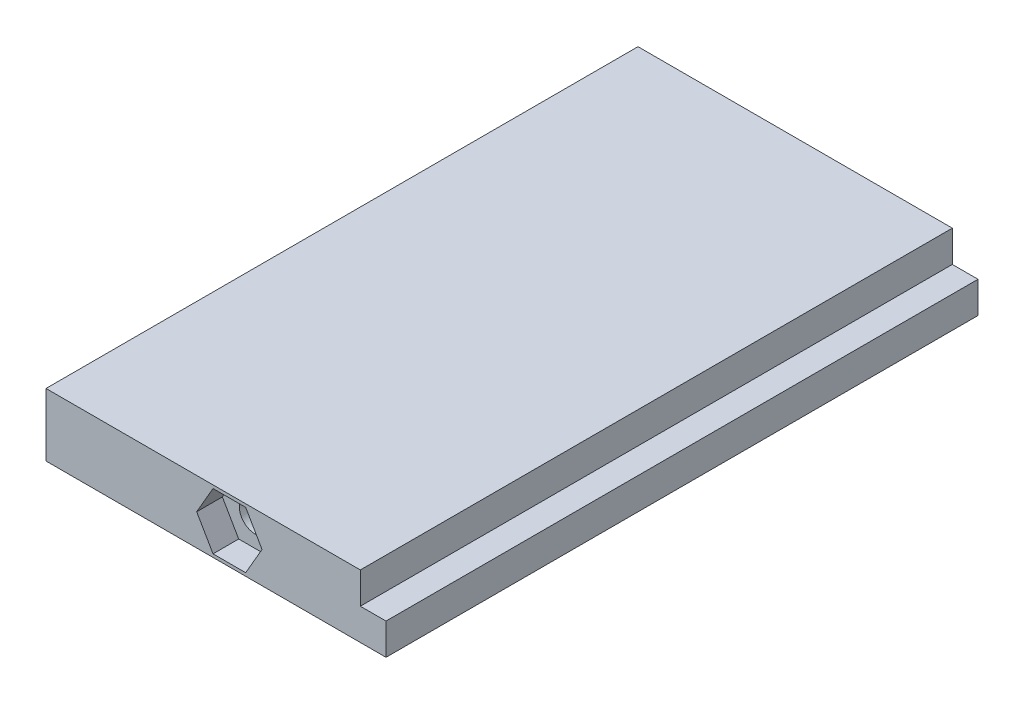
SolidWorks part; units mm, degrees
ref_plane "Front Plane" through (0, 0, 0) normal (0, 0, 1) x (1, 0, 0)
ref_plane "Top Plane" through (0, 0, 0) normal (0, 1, 0) x (1, 0, 0)
ref_plane "Right Plane" through (0, 0, 0) normal (1, 0, 0) x (0, 0, -1)
sketch "Sketch1" plane through (0, 0, 0) normal (0, 1, 0) x (1, 0, 0)
  line L1 (-15, 28.25) -> (15, 28.25)
  line L2 (-15, 28.25) -> (-15, -28.25)
  line L3 (-15, -28.25) -> (15, -28.25)
  line L4 (15, 28.25) -> (15, -28.25)
  line L5 (-15, 28.25) -> (15, -28.25) construction
  line L6 (-15, -28.25) -> (15, 28.25) construction
  point P4 (0, 0)
  point P5 (0, 0)
  point P6 (36.1808, 26.0547)
  point P7 (0, 0)
  dimension "D1" = 56.5
  dimension "D2" = 30
extrude "Boss-Extrude1" add sketch "Sketch1" along normal blind 6
sketch "Sketch8" plane through (15, 0, 0) normal (1, 0, 0) x (0, 0, -1)
  line L0 (-28.25, 6) -> (-28.25, 0) construction
  line L1 (-28.25, 3) -> (28.25, 3)
  line L2 (-28.25, 3) -> (-28.25, 0)
  line L3 (-28.25, 0) -> (28.25, 0)
  line L4 (28.25, 3) -> (28.25, 0)
  line L5 (-28.25, 3) -> (28.25, 0) construction
  line L6 (-28.25, 0) -> (28.25, 3) construction
  line L7 (16.5, 0) -> (-16.5, 0) construction
  line L8 (28.25, 6) -> (28.25, 0) construction
  point P4 (0, 1.5)
  point P9 (-28.25, 3)
  point P10 (28.25, 3)
extrude "Boss-Extrude3" add sketch "Sketch8" along normal blind 2.45
sketch "Sketch9" plane through (0, 0, -28.25) normal (0, 0, -1) x (-1, 0, 0)
  line L0 (-15, 6) -> (15, 6) construction
  line L1 (-15, 6) -> (-15, 3) construction
  circle A0 centre (-2.5, 3) radius 1.5
  dimension "D1" = 3
  dimension "D3" = 3
  dimension "D2" = 12.5
extrude "Cut-Extrude3" cut sketch "Sketch9" against normal through all
sketch "Sketch10" plane through (0, 0, -28.25) normal (0, 0, -1) x (-1, 0, 0)
  line L1 (-0.9412, 0.3) -> (0.6177, 3)
  line L2 (0.6177, 3) -> (-0.9412, 5.7)
  line L3 (-0.9412, 5.7) -> (-4.0588, 5.7)
  line L4 (-4.0588, 5.7) -> (-5.6177, 3)
  line L5 (-5.6177, 3) -> (-4.0588, 0.3)
  line L6 (-4.0588, 0.3) -> (-0.9412, 0.3)
  line L8 (-15, 6) -> (15, 6) construction
  circle A0 centre (-2.5, 3) radius 2.7 construction
  point P1 (0.6177, 3)
  dimension "D1" = 5.4
extrude "Cut-Extrude4" cut sketch "Sketch10" against normal blind 2.45
mirror "Mirror2" about plane through (0, 0, 0) normal (0, 0, 1) of "Cut-Extrude4"
